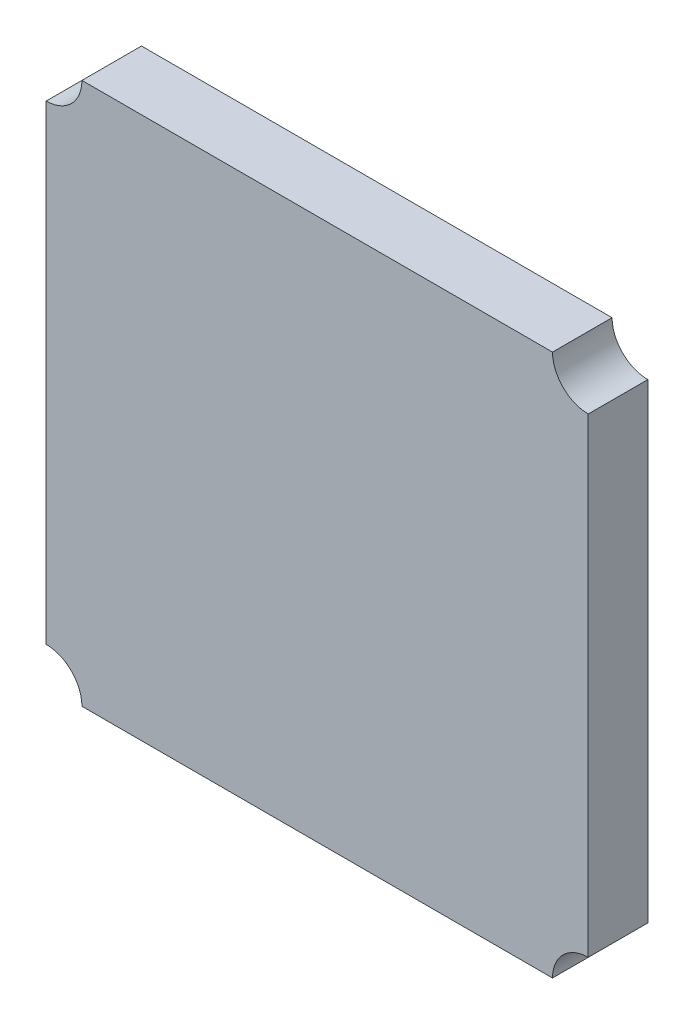
SolidWorks part; units mm, degrees
ref_plane "Plan de face" through (0, 0, 0) normal (0, 0, 1) x (1, 0, 0)
ref_plane "Plan de dessus" through (0, 0, 0) normal (0, 1, 0) x (1, 0, 0)
ref_plane "Plan de droite" through (0, 0, 0) normal (1, 0, 0) x (0, 0, -1)
sketch "Esquisse1" plane through (0, 0, 0) normal (0, 0, 1) x (1, 0, 0)
  line L1 (0, 0) -> (45.5, 0)
  line L2 (0, 0) -> (0, -45.5)
  line L3 (0, -45.5) -> (45.5, -45.5)
  line L4 (45.5, 0) -> (45.5, -45.5)
  arc A1 (3, -45.5) -> (0, -42.5) centre (0, -45.5) ccw
  arc A2 (42.5, -45.5) -> (45.5, -42.5) centre (45.5, -45.5) cw
  arc A3 (45.5, -3) -> (42.5, 0) centre (45.5, 0) cw
  arc A4 (0, -3) -> (3, 0) centre (0, 0) ccw
  dimension "D1" = 45.5
  dimension "D2" = 45.5
  dimension "D3" = 3
  dimension "D4" = 3
  dimension "D5" = 3
  dimension "D6" = 3
extrude "Boss.-Extru.1" add sketch "Esquisse1" along normal blind 5 contours A4 L2 A1 L3 A2 L4 A3 L1
